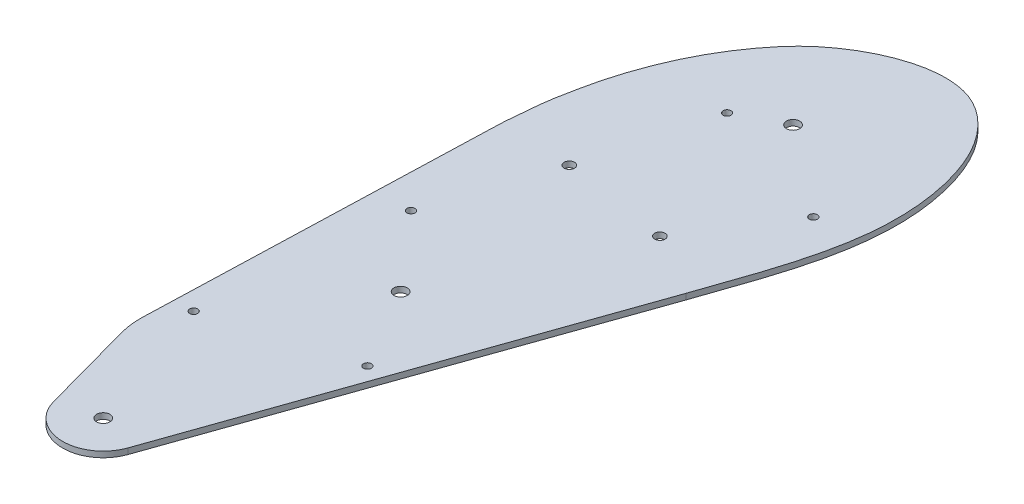
SolidWorks part; units mm, degrees
material "2024-T3"
ref_plane "Front Plane" through (0, 0, 0) normal (0, 0, 1) x (1, 0, 0)
ref_plane "Top Plane" through (0, 0, 0) normal (0, 1, 0) x (1, 0, 0)
ref_plane "Right Plane" through (0, 0, 0) normal (1, 0, 0) x (0, 0, -1)
sketch "Sketch1" plane through (0, 0, 0) normal (0, 1, 0) x (1, 0, 0)
  line L0 (-82.9198, -128.6989) -> (-29.1406, 24.3174)
  line L1 (-116.7951, 57.8545) -> (-117.8844, 45.8503)
  line L2 (-118.0806, 40.9832) -> (-122.1478, -84.0107)
  line L3 (-121.0907, -92.9381) -> (-111.5347, -127.7011)
  arc A0 (-122.1478, -84.0107) -> (-121.0907, -92.9381) centre (-92.1637, -84.9864) ccw
  arc A1 (-111.5347, -127.7011) -> (-82.9198, -128.6989) centre (-97.0712, -123.7252) ccw
  circle A2 centre (-97.0712, -123.7252) radius 2.455
  circle A3 centre (-114.6018, -72.6579) radius 1.475
  circle A4 centre (-64.8432, -58.0439) radius 1.475
  circle A5 centre (-82.5395, -28.0465) radius 2.455
  circle A6 centre (-106.6182, -0.1142) radius 1.475
  circle A7 centre (-52.3077, 37.8106) radius 1.925
  circle A8 centre (-91.8542, 43.817) radius 1.925
  circle A9 centre (-30.0412, 72.4274) radius 1.475
  circle A10 centre (-79.4087, 89.8142) radius 1.475
  circle A11 centre (-63.3611, 98.226) radius 2.455
  spline S0 degree 3 poles (-29.1406, 24.3174) (-23.3379, 41.2771) (-12.8599, 68.4621) (-14.3199, 106.433) (-23.5393, 129.0541) (-49.2899, 148.4052) (-78.0318, 135.5765) (-101.1521, 109.2917) (-108.9509, 92.7295) (-113.165, 76.6768) knots 0.130451 0.130451 0.130451 0.130451 0.339996 0.443939 0.557713 0.600921 0.796564 0.817312 1 1 1 1
  spline S1 degree 3 poles (-113.165, 76.6768) (-114.2933, 72.0493) (-115.2402, 67.389) (-116.0869, 62.766) knots 0.013286 0.013286 0.013286 0.013286 0.075218 0.075218 0.075218 0.075218
  spline S2 degree 3 poles (-116.0869, 62.766) (-116.3485, 61.136) (-116.5845, 59.4984) (-116.7951, 57.8545) knots 0.060716 0.060716 0.060716 0.060716 0.078642 0.078642 0.078642 0.078642
  spline S3 degree 3 poles (-117.8844, 45.8503) (-117.9726, 44.2306) (-118.0379, 42.6078) (-118.0806, 40.9832) knots 0 0 0 0 0.017419 0.017419 0.017419 0.017419
extrude "Boss-Extrude1" add sketch "Sketch1" along normal blind 2.15
